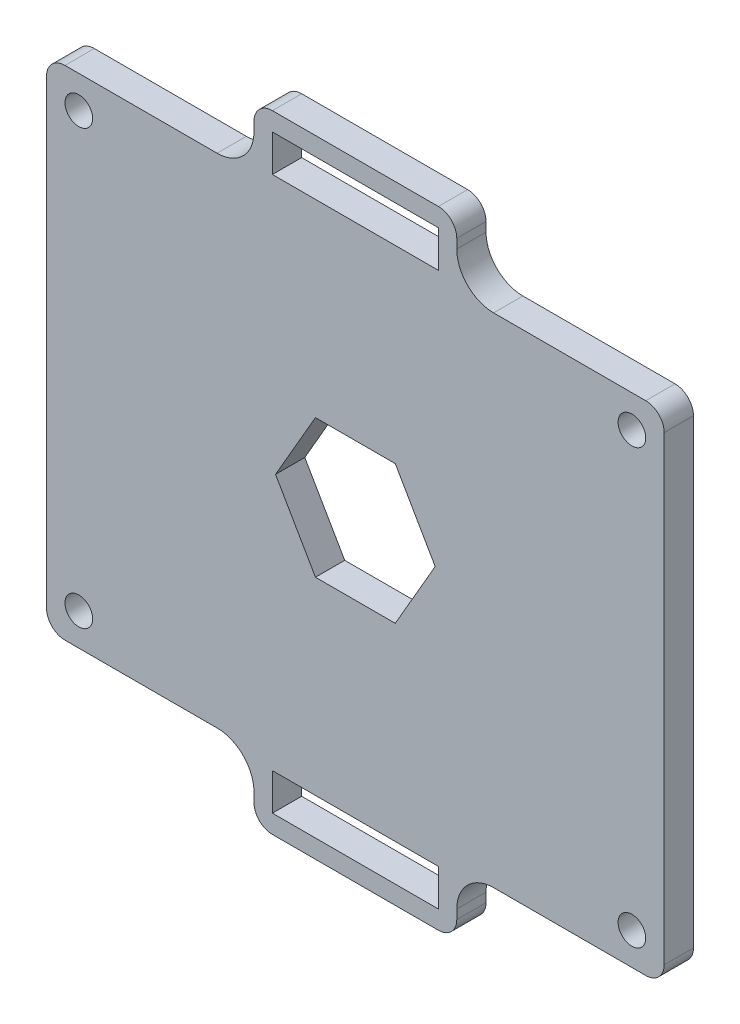
SolidWorks part; units mm, degrees
ref_plane "Front Plane" through (0, 0, 0) normal (0, 0, 1) x (1, 0, 0)
ref_plane "Top Plane" through (0, 0, 0) normal (0, 1, 0) x (1, 0, 0)
ref_plane "Right Plane" through (0, 0, 0) normal (1, 0, 0) x (0, 0, -1)
sketch "Sketch1" plane through (0, 0, 0) normal (0, 0, 1) x (1, 0, 0)
  line L0 (-33.5, 27) -> (33.5, -27) construction
  line L1 (-33.5, 27) -> (-11, 27)
  line L2 (-33.5, 27) -> (-33.5, -27)
  line L3 (-33.5, -27) -> (-11, -27)
  line L4 (33.5, 27) -> (33.5, -27)
  line L5 (-30, -23.5) -> (30, 23.5) construction
  line L6 (-30, 23.5) -> (30, 23.5) construction
  line L7 (-30, 23.5) -> (-30, -23.5) construction
  line L8 (-30, -23.5) -> (30, -23.5) construction
  line L9 (30, 23.5) -> (30, -23.5) construction
  line L10 (0, 27) -> (0, -27) construction
  line L11 (-11, 34) -> (11, 34)
  line L12 (-11, 34) -> (-11, 27)
  line L13 (11, -27) -> (33.5, -27)
  line L14 (11, 34) -> (11, 27)
  line L15 (-9, -28) -> (9, -28)
  line L16 (-11, -27) -> (-11, -34)
  line L17 (-11, -34) -> (11, -34)
  line L18 (11, -27) -> (11, -34)
  line L19 (11, 27) -> (33.5, 27)
  line L20 (-9, 32) -> (9, 32)
  line L21 (-9, 32) -> (-9, 28)
  line L22 (-9, 28) -> (9, 28)
  line L23 (9, 32) -> (9, 28)
  line L24 (-9, -28) -> (-9, -32)
  line L25 (-9, -32) -> (9, -32)
  line L26 (9, -28) -> (9, -32)
  line L27 (0, 32) -> (0, 34) construction
  line L28 (0, -32) -> (0, -34) construction
  line L30 (8.6603, 0) -> (4.3301, 7.5)
  line L31 (4.3301, 7.5) -> (-4.3301, 7.5)
  line L32 (-4.3301, 7.5) -> (-8.6603, 0)
  line L33 (-8.6603, 0) -> (-4.3301, -7.5)
  line L34 (-4.3301, -7.5) -> (4.3301, -7.5)
  line L35 (4.3301, -7.5) -> (8.6603, 0)
  circle A0 centre (-30, 23.5) radius 1.5
  circle A1 centre (30, 23.5) radius 1.5
  circle A2 centre (30, -23.5) radius 1.5
  circle A3 centre (-30, -23.5) radius 1.5
  circle A4 centre (0, 0) radius 7.5 construction
  point P4 (0, 0)
  point P10 (0, 0)
  point P37 (0, 34)
  point P38 (0, -34)
  dimension "D5" = 3
  dimension "D13" = 15
  dimension "D1" = 54
  dimension "D2" = 67
  dimension "D3" = 47
  dimension "D4" = 60
  dimension "D6" = 22
  dimension "D7" = 7
  dimension "D8" = 18
  dimension "D9" = 4
  dimension "D10" = 18
  dimension "D11" = 4
  dimension "D12" = 2
extrude "Boss-Extrude1" add sketch "Sketch1" along normal blind 3.175
fillet "Fillet1" radius 4 4 edges at (-11, 27, 1.5875) (11, 27, 1.5875) (11, -27, 1.5875) (-11, -27, 1.5875)
fillet "Fillet2" radius 2 8 edges at (11, 34, 1.5875) (33.5, 27, 1.5875) (33.5, -27, 1.5875) (11, -34, 1.5875) (-11, -34, 1.5875) (-33.5, -27, 1.5875) (-33.5, 27, 1.5875) (-11, 34, 1.5875)
